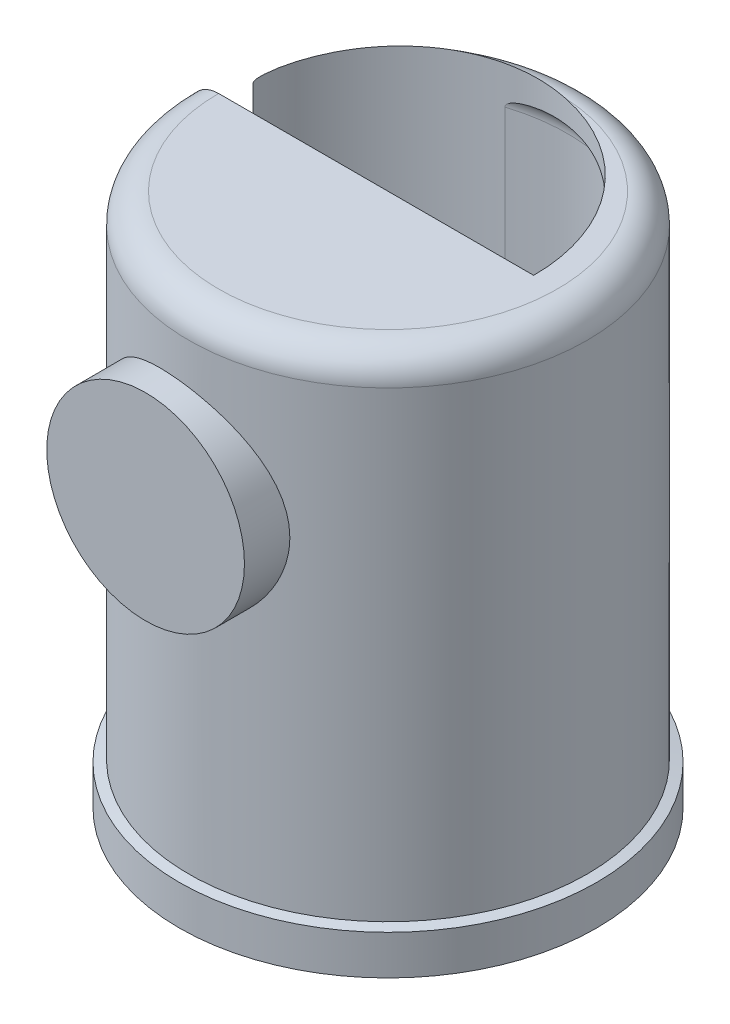
SolidWorks part; units mm, degrees
ref_plane "Front Plane" through (0, 0, 0) normal (0, 0, 1) x (1, 0, 0)
ref_plane "Top Plane" through (0, 0, 0) normal (0, 1, 0) x (1, 0, 0)
ref_plane "Right Plane" through (0, 0, 0) normal (1, 0, 0) x (0, 0, -1)
sketch "Sketch1" plane through (0, 0, 0) normal (0, 0, 1) x (1, 0, 0)
  line L0 (2.7649, 7.8218) -> (2.7649, 58.3592) construction
  line L1 (20.9, 0) -> (23.8716, 0)
  line L2 (23.8716, 0) -> (23.8716, 4)
  line L3 (23.8716, 4) -> (22.9, 4.2367)
  line L4 (22.9, 4.2367) -> (22.9, 51)
  line L6 (20.9, 0) -> (20.9, 15)
  line L7 (18.9, 52) -> (2.7649, 52)
  line L8 (2.7649, 52) -> (2.7649, 54)
  line L9 (20.9, 17) -> (20.9, 50)
  line L10 (20.9, 17) -> (2.7649, 17)
  line L12 (20.9, 15) -> (2.7649, 15)
  line L13 (2.7649, 17) -> (2.7649, 15)
  line L14 (19.9, 54) -> (2.7649, 54)
  arc A1 (20.9, 50) -> (18.9, 52) centre (18.9, 50) ccw
  arc A2 (22.9, 51) -> (19.9, 54) centre (19.9, 51) ccw
  point P11 (22.9, 54)
  dimension "D9" = 2
  dimension "D4" = 3
  dimension "D1" = 2
  dimension "D2" = 4
  dimension "D3" = 1
  dimension "D6" = 2
  dimension "D7" = 2.9716
  dimension "D10" = 2
  dimension "D11" = 15
  dimension "D12" = 35
  dimension "D13" = 37
revolve "Revolve1" add sketch "Sketch1" angle 360 about L0
ref_plane "Plane1" through (0, 4, 0) normal (0, 1, 0) x (1, 0, 0)
sketch "Sketch3" plane through (0, 0, 0) normal (0, 0, 1) x (1, 0, 0)
  point P0 (1.2404, 19.1989)
ref_point "Point1"
ref_plane "Plane2" through (0, 0, 22.9) normal (0, 0, 1) x (1, 0, 0)
sketch "Sketch4" plane through (0, 0, 22.9) normal (0, 0, 1) x (1, 0, 0)
  line L1 (22.9, 51) -> (-17.3702, 51) construction
  circle A1 centre (1.1446, 37) radius 10
  dimension "D1" = 20
  dimension "D2" = 14
extrude "Boss-Extrude2" add sketch "Sketch4" against normal blind 6
ref_plane "Plane3" through (0, 0, 16.9) normal (0, 0, -1) x (-1, 0, 0)
ref_plane "Plane4" through (0, 54, 0) normal (0, 1, 0) x (1, 0, 0)
sketch "Sketch9" plane through (0, 54, 0) normal (0, 1, 0) x (1, 0, 0)
  line L0 (-17.5, 0) -> (17.5, 0)
  arc A0 (17.5, 0) -> (-17.5, 0) centre (0, 0) ccw
  dimension "D1" = 35
extrude "Cut-Extrude2" cut sketch "Sketch9" against normal blind 30
